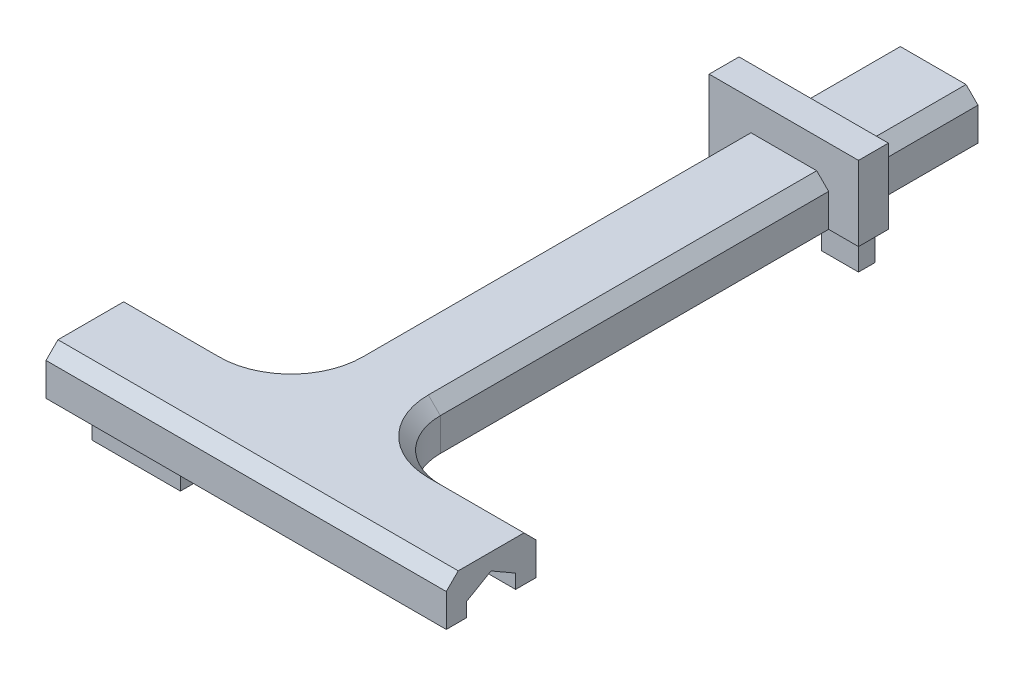
SolidWorks part; units mm, degrees
ref_plane "Front Plane" through (0, 0, 0) normal (0, 0, 1) x (1, 0, 0)
ref_plane "Top Plane" through (0, 0, 0) normal (0, 1, 0) x (1, 0, 0)
ref_plane "Right Plane" through (0, 0, 0) normal (1, 0, 0) x (0, 0, -1)
sketch "Sketch1" plane through (0, 0, 0) normal (0, 1, 0) x (1, 0, 0)
  line L0 (0, 0) -> (0, 15)
  line L1 (0, 15) -> (16, 15)
  line L2 (41, 25) -> (41, 115)
  line L3 (41, 115) -> (26, 115)
  line L4 (26, 115) -> (26, 25)
  line L5 (51, 15) -> (67, 15)
  line L6 (67, 15) -> (67, 0)
  line L7 (67, 0) -> (0, 0)
  arc A0 (26, 25) -> (16, 15) centre (16, 25) cw
  arc A1 (51, 15) -> (41, 25) centre (51, 25) cw
  point P10 (33.5, 115)
  point P11 (33.5, 0)
  point P16 (41, 15)
  dimension "D5" = 10
  dimension "D1" = 15
  dimension "D2" = 67
  dimension "D3" = 100
  dimension "D4" = 15
extrude "Boss-Extrude1" add sketch "Sketch1" along normal blind 7.5 contours L3 L4 L1 L2 | L7 L6 L5 L1 L0
sketch "Sketch2" plane through (0, 7.5, 0) normal (0, 1, 0) x (1, 0, 0)
  line L0 (33.5, 115) -> (33.5, 7.5)
  line L1 (41, 115) -> (26, 115) construction
  line L2 (33.5, 7.5) -> (67, 7.5)
  line L3 (67, 15) -> (67, 0) construction
  point P8 (67, 7.5)
sketch "Sketch3" plane through (0, 0, -115) normal (0, 0, -1) x (-1, 0, 0)
  line L0 (-41, 7.5) -> (-26, 7.5) construction
  line L1 (-37.6, 5.1329) -> (-33.5, 2.7657)
  line L2 (-33.5, 2.7657) -> (-29.4, 5.1329)
  line L3 (-29.4, 5.1329) -> (-29.4, 9.8671)
  line L4 (-29.4, 9.8671) -> (-33.5, 12.2343)
  line L5 (-33.5, 12.2343) -> (-37.6, 9.8671)
  line L6 (-37.6, 9.8671) -> (-37.6, 5.1329)
  circle A0 centre (-33.5, 7.5) radius 4.1 construction
  dimension "D1" = 8.2
sweep "Cut-Sweep1" cut profiles "Sketch3" path "Sketch2"
sketch "Sketch7" plane through (0, 7.5, 0) normal (0, 1, 0) x (1, 0, 0)
  line L5 (47.6, 11.6) -> (47.6, 3.4)
  line L6 (67, 3.4) -> (29.4, 3.4) construction
  line L7 (47.6, 3.4) -> (29.4, 3.4)
  line L8 (29.4, 3.4) -> (29.4, 21.6)
  line L14 (37.6, 115) -> (37.6, 11.6) construction
  line L19 (29.4, 21.6) -> (37.6, 21.6)
  line L20 (29.4, 115) -> (29.4, 3.4) construction
  line L21 (37.6, 115) -> (37.6, 11.6) construction
  line L22 (37.6, 21.6) -> (37.6, 20.6)
  line L23 (46.6, 11.6) -> (47.6, 11.6)
  line L24 (37.6, 11.6) -> (67, 11.6) construction
  arc A0 (37.6, 20.6) -> (46.6, 11.6) centre (46.6, 20.6) ccw
  point P16 (37.6, 11.6)
  dimension "D3" = 9
  dimension "D1" = 10
  dimension "D2" = 10
extrude "Cut-Extrude6" cut sketch "Sketch7" against normal blind 5
sketch "Sketch10" plane through (0, 0, -115) normal (0, 0, -1) x (-1, 0, 0)
  line L0 (-46, 7.5) -> (-21, 7.5)
  line L1 (-46, 7.5) -> (-46, -5)
  line L2 (-21, 7.5) -> (-21, -5)
  line L3 (-46, -5) -> (-21, -5)
  line L4 (-51, 7.5) -> (-67, 7.5) construction
  line L5 (0, 7.5) -> (-16, 7.5) construction
  line L7 (-41, 0) -> (-26, 0) construction
  line L9 (-41, 7.5) -> (-26, 7.5)
  line L10 (-41, 7.5) -> (-41, 0)
  line L11 (-41, 0) -> (-26, 0)
  line L12 (-26, 7.5) -> (-26, 0)
  point P10 (-33.5, 0)
  point P11 (-33.5, -5)
  line M10 (-41, 7.5) -> (-41, 0)
  line M11 (-41, 0) -> (-26, 0)
  line M12 (-26, 0) -> (-26, 7.5)
  dimension "D1" = 25
  dimension "D2" = 12.5
extrude "Boss-Extrude2" add sketch "Sketch10" against normal blind 5 from offset 20 contours L1 L3 L2 L0 M12 M11 M10 offset against normal yes
chamfer "Chamfer1" distance 2 angle 45 9 edges at (33.5, 0, 0) (8, 0, -15) (26, 0, -57.5) (59, 0, -15) (41, 0, -57.5) (26, 0, -105) (41, 0, -105) (23.0711, 0, -17.9289) (43.9289, 0, -17.9289)
sketch "Sketch11" plane through (0, 7.5, 0) normal (0, 1, 0) x (1, 0, 0)
  line L0 (5.1, 12.4) -> (5.1, 2.6)
  line L1 (5, 12.5) -> (20, 12.5)
  line L2 (5, 12.5) -> (5, 2.5)
  line L3 (5, 2.5) -> (20, 2.5)
  line L4 (20, 12.5) -> (20, 2.5)
  line L5 (0, 0) -> (0, 15) construction
  line L6 (26, 90) -> (21, 90) construction
  line L7 (22, 94) -> (28.4, 94)
  line L8 (22, 94) -> (22, 91)
  line L9 (22, 91) -> (28.4, 91)
  line L10 (28.4, 94) -> (28.4, 91)
  line L11 (21, 90) -> (21, 95) construction
  line L12 (29.4, 3.4) -> (29.4, 115) construction
  line L13 (33.5, 115) -> (33.5, 0) construction
  line L14 (67, 0) -> (0, 0) construction
  line L15 (38.6, 94) -> (38.6, 91)
  line L16 (45, 91) -> (38.6, 91)
  line L17 (45, 94) -> (45, 91)
  line L18 (45, 94) -> (38.6, 94)
  line L19 (5.1, 2.6) -> (19.9, 2.6)
  line L20 (19.9, 12.4) -> (19.9, 2.6)
  line L21 (5.1, 12.4) -> (19.9, 12.4)
  line L22 (22.1, 93.9) -> (22.1, 91.1)
  line L23 (22.1, 91.1) -> (28.3, 91.1)
  line L24 (28.3, 93.9) -> (28.3, 91.1)
  line L25 (22.1, 93.9) -> (28.3, 93.9)
  line L26 (38.7, 93.9) -> (38.7, 91.1)
  line L27 (44.9, 91.1) -> (38.7, 91.1)
  line L28 (44.9, 93.9) -> (44.9, 91.1)
  line L29 (44.9, 93.9) -> (38.7, 93.9)
  point P6 (0, 7.5)
  point P7 (5, 7.5)
  point P18 (21, 92.5)
  point P19 (22, 92.5)
  dimension "D1" = 10
  dimension "D2" = 15
  dimension "D3" = 5
  dimension "D4" = 1
  dimension "D5" = 1
  dimension "D6" = 1
  dimension "D7" = 0.1
  dimension "D8" = 0.1
  dimension "D9" = 0.1
extrude "Boss-Extrude3" add sketch "Sketch11" along normal blind 4.8 contours L21 L0 L19 L20 | L25 L22 L23 L24 | L28 L29 L26 L27
mirror "Mirror1" about plane through (0, 7.5, 0) normal (0, 1, 0) of bodies 111
delete or keep bodies "Body-Delete/Keep 1" type delete bodies bodies 111
